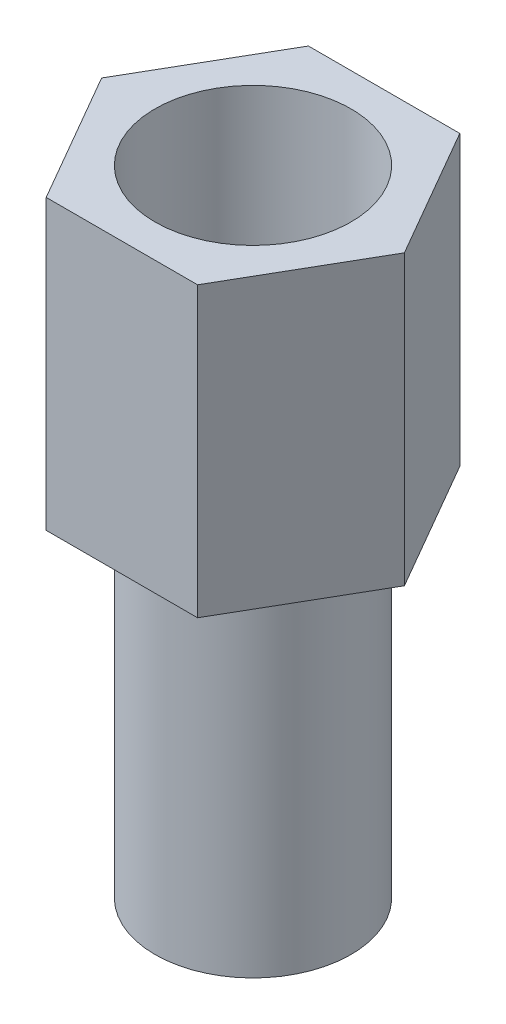
SolidWorks part; units mm, degrees
ref_plane "前视基准面" through (0, 0, 0) normal (0, 0, 1) x (1, 0, 0)
ref_plane "上视基准面" through (0, 0, 0) normal (0, 1, 0) x (1, 0, 0)
ref_plane "右视基准面" through (0, 0, 0) normal (1, 0, 0) x (0, 0, -1)
sketch "草图1" plane through (0, 0, 0) normal (0, 1, 0) x (1, 0, 0)
  line L2 (1.3125, -2.2733) -> (2.625, 0)
  line L4 (1.3125, 2.2733) -> (-1.3125, 2.2733)
  line L5 (-1.3125, 2.2733) -> (-2.625, 0)
  line L6 (1.3125, 2.2733) -> (2.625, 0)
  line L7 (1.3125, -2.2733) -> (-1.3125, -2.2733)
  line L8 (-1.3125, -2.2733) -> (-2.625, 0)
extrude "凸台-拉伸1" add sketch "草图1" along normal blind 5
sketch "草图2" plane through (0, 0, 0) normal (0, 1, 0) x (1, 0, 0)
  circle A0 centre (0, 0) radius 1.7
extrude "凸台-拉伸2" add sketch "草图2" against normal blind 6
sketch "草图3" plane through (0, 5, 0) normal (0, 1, 0) x (1, 0, 0)
  circle A0 centre (0, 0) radius 1.7
extrude "切除-拉伸1" cut sketch "草图3" against normal blind 4
